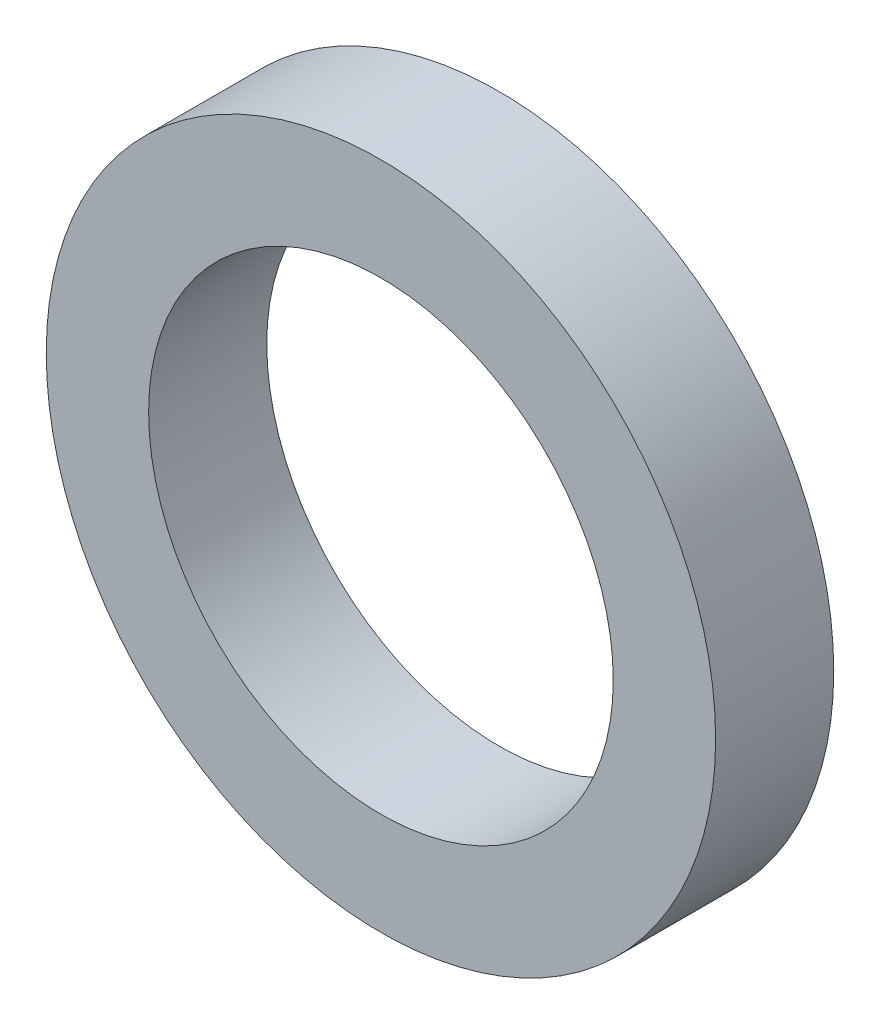
SolidWorks part; units mm, degrees
material "POLYURETHANE (11671)"
ref_plane "Plano frontal" through (0, 0, 0) normal (0, 0, 1) x (1, 0, 0)
ref_plane "Plano superior" through (0, 0, 0) normal (0, 1, 0) x (1, 0, 0)
ref_plane "Plano direito" through (0, 0, 0) normal (1, 0, 0) x (0, 0, -1)
sketch "Sketch1" plane through (0, 0, 0) normal (0, 0, 1) x (1, 0, 0)
  circle A0 centre (0, 0) radius 29.5
  circle A1 centre (0, 0) radius 42.5
  dimension "D1" = 59
  dimension "D2" = 85
extrude "Boss-Extrude1" add sketch "Sketch1" against normal blind 15
